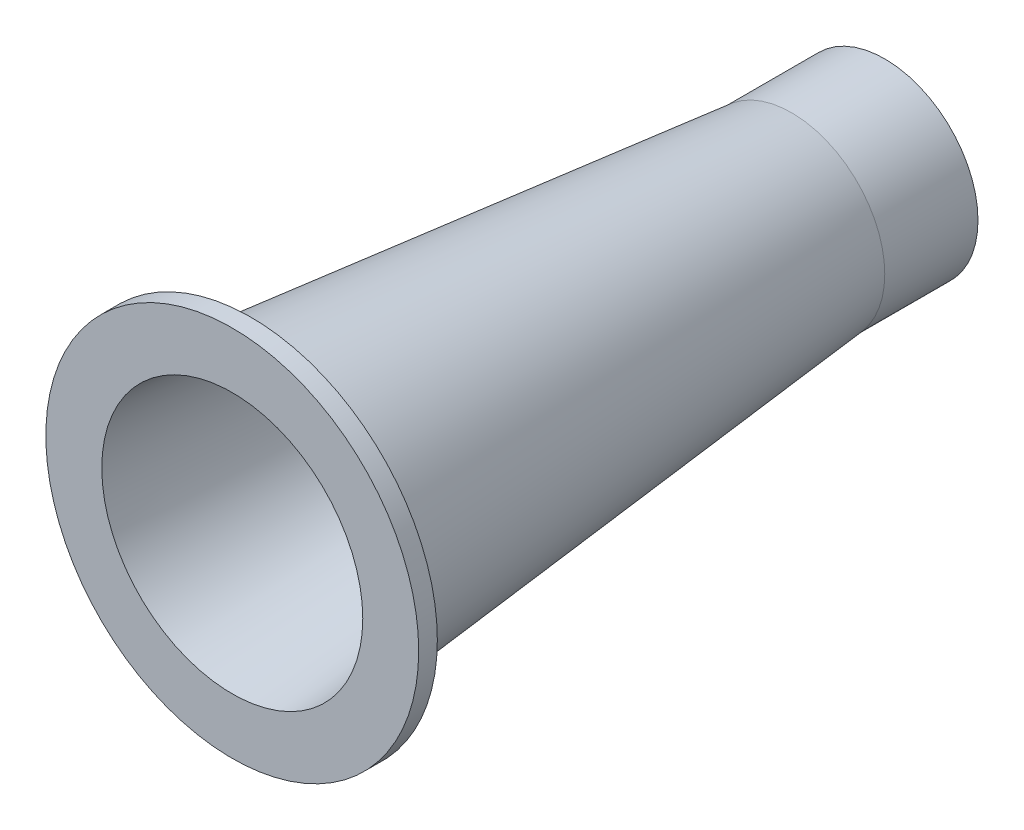
SolidWorks part; units mm, degrees
ref_plane "Front Plane" through (0, 0, 0) normal (0, 0, 1) x (1, 0, 0)
ref_plane "Top Plane" through (0, 0, 0) normal (0, 1, 0) x (1, 0, 0)
ref_plane "Right Plane" through (0, 0, 0) normal (1, 0, 0) x (0, 0, -1)
sketch "Sketch1" plane through (0, 0, 0) normal (0, 1, 0) x (1, 0, 0)
  line L0 (0, -396.0409) -> (0, 700) construction
  line L1 (60, 700) -> (100, 700)
  line L2 (100, 700) -> (100, 600)
  line L3 (60, 700) -> (60, 599.8893)
  line L4 (60, 599.8893) -> (75.3868, 599.8893)
  line L5 (80.3619, 595.3876) -> (140, 0)
  line L6 (140, 0) -> (200, 0)
  line L7 (200, 0) -> (200, 20)
  line L8 (200, 20) -> (158.0967, 20)
  line L9 (158.0967, 20) -> (100, 600)
  arc A0 (75.3868, 599.8893) -> (80.3619, 595.3876) centre (75.3868, 594.8893) cw
  dimension "D9" = 5
  dimension "D1" = 700
  dimension "D2" = 60
  dimension "D3" = 100
  dimension "D4" = 100
  dimension "D5" = 140
  dimension "D6" = 20
  dimension "D7" = 20
  dimension "D8" = 200
revolve "Revolve1" add sketch "Sketch1" angle 360 about L0
sketch "Sketch2" plane through (0, 0, 0) normal (0, 1, 0) x (1, 0, 0)
  line L0 (60, 700) -> (-60, 700) construction
  circle A0 centre (0, 660) radius 3
  dimension "D2" = 6
  dimension "D1" = 40
extrude "Cut-Extrude1" cut sketch "Sketch2" against normal through all
